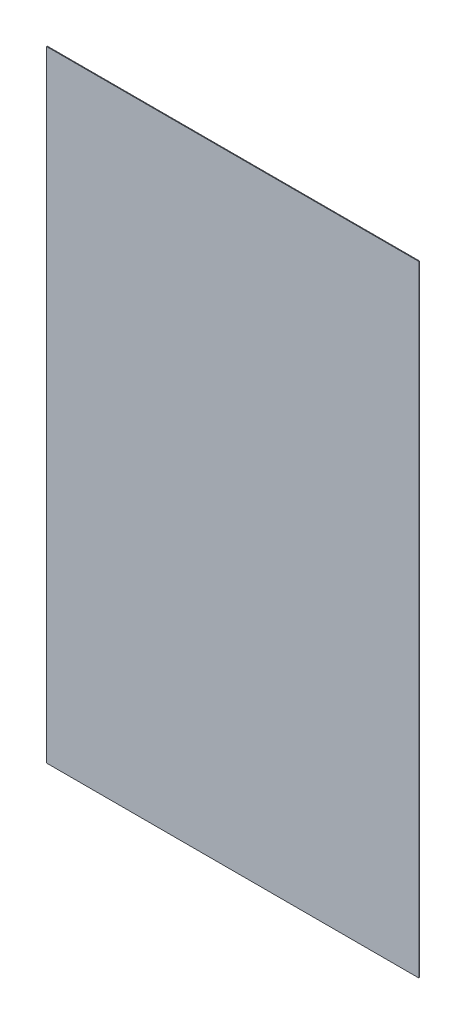
SolidWorks part; units mm, degrees
ref_plane "前基準面" through (0, 0, 0) normal (0, 0, 1) x (1, 0, 0)
ref_plane "上基準面" through (0, 0, 0) normal (0, 1, 0) x (1, 0, 0)
ref_plane "右基準面" through (0, 0, 0) normal (1, 0, 0) x (0, 0, -1)
sketch "草圖1" plane through (0, 0, 0) normal (0, 0, 1) x (1, 0, 0)
  line L1 (0, 0) -> (1500, 0)
  line L2 (0, 0) -> (0, -2500)
  line L3 (0, -2500) -> (1500, -2500)
  line L4 (1500, 0) -> (1500, -2500)
  dimension "D1" = 1500
  dimension "D2" = 2500
extrude "填料-伸長1" add sketch "草圖1" along normal blind 3
sketch "草圖2" plane through (0, 0, 3) normal (0, 0, 1) x (1, 0, 0)
  line L0 (750, 0) -> (750, -2500) construction
  line L1 (1500, 0) -> (0, 0) construction
  line L2 (0, -2500) -> (1500, -2500) construction
  circle A0 centre (750, -1300) radius 20
  dimension "D1" = 1200
  dimension "D2" = 40
extrude "除料-伸長1" [suppressed] cut sketch "草圖2" against normal through all
